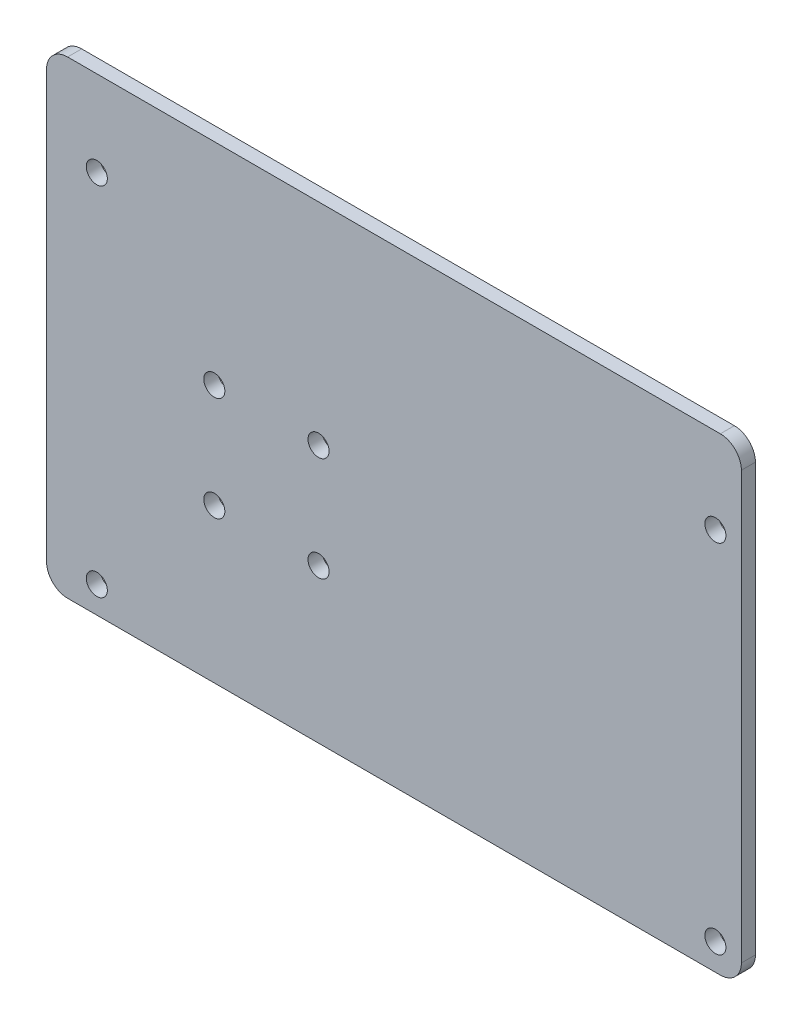
SolidWorks part; units mm, degrees
material "PBT 一般用途"
ref_plane "前视基准面" through (0, 0, 0) normal (0, 0, 1) x (1, 0, 0)
ref_plane "上视基准面" through (0, 0, 0) normal (0, 1, 0) x (1, 0, 0)
ref_plane "右视基准面" through (0, 0, 0) normal (1, 0, 0) x (0, 0, -1)
other "Configuration Table"
sketch "草图1" plane through (0, 0, 0) normal (0, 0, 1) x (1, 0, 0)
  line L1 (-49.0704, 26.2936) -> (43.9296, 26.2936)
  line L2 (-52.0704, 23.2936) -> (-52.0704, -37.5064)
  line L3 (-49.0704, -40.5064) -> (43.9296, -40.5064)
  line L4 (46.9296, 23.2936) -> (46.9296, -37.5064)
  arc A0 (46.9296, 23.2936) -> (43.9296, 26.2936) centre (43.9296, 23.2936) ccw
  arc A1 (43.9296, -40.5064) -> (46.9296, -37.5064) centre (43.9296, -37.5064) ccw
  arc A2 (-49.0704, -40.5064) -> (-52.0704, -37.5064) centre (-49.0704, -37.5064) cw
  arc A3 (-52.0704, 23.2936) -> (-49.0704, 26.2936) centre (-49.0704, 23.2936) cw
  point P6 (46.9296, 26.2936)
  point P11 (-52.0704, -40.5064)
  point P14 (-52.0704, 26.2936)
  dimension "D3" = 3
  dimension "D1" = 66.8
  dimension "D2" = 99
extrude "凸台-拉伸1" add sketch "草图1" along normal blind 2
sketch "草图2" plane through (0, 0, 2) normal (0, 0, 1) x (1, 0, 0)
  line L0 (43.9296, 26.2936) -> (-49.0704, 26.2936) construction
  line L1 (-52.0704, 23.2936) -> (-52.0704, -37.5064) construction
  line L2 (-49.0704, -40.5064) -> (43.9296, -40.5064) construction
  circle A0 centre (-44.9144, 14.1016) radius 1.5
  circle A1 centre (43.2256, 14.1016) radius 1.5
  circle A2 centre (-44.9144, -36.6984) radius 1.5
  circle A3 centre (43.2256, -36.6984) radius 1.5
  circle A4 centre (-28.1704, -3.7451) radius 1.5
  circle A5 centre (-28.1704, -18.5944) radius 1.5
  circle A6 centre (-13.3212, -3.7451) radius 1.5
  circle A7 centre (-13.3212, -18.5944) radius 1.5
  point P0 (-44.9144, 14.1016)
  point P5 (43.2256, 14.1016)
  point P6 (-44.9144, -36.6984)
  point P7 (43.2256, -36.6984)
  point P16 (-28.1704, -18.5944)
  point P17 (-13.3212, -18.5944)
  point P18 (-28.1704, -3.7451)
  point P22 (-13.3212, -3.7451)
  dimension "D7" = 23.9
  dimension "D1" = 12.192
  dimension "D2" = 7.156
  dimension "D3" = 88.14
  dimension "D4" = 50.8
  dimension "D5" = 50.8
  dimension "D6" = 88.14
  dimension "D8" = 21.912
  dimension "D9" = 14.8492
  dimension "D10" = 21
  dimension "D11" = 14.8492
  dimension "D12" = 14.8492
extrude "切除-拉伸1" cut sketch "草图2" against normal blind 2
